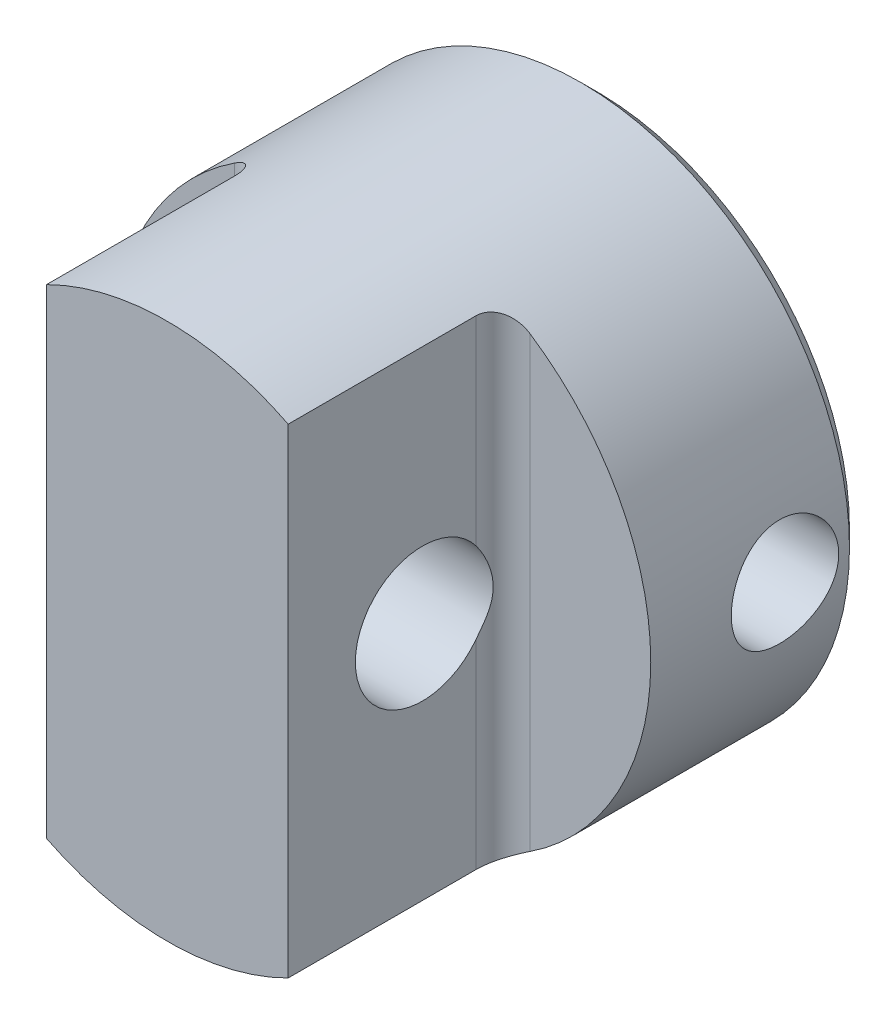
SolidWorks part; units mm, degrees
ref_plane "Спереди" through (0, 0, 0) normal (0, 0, 1) x (1, 0, 0)
ref_plane "Сверху" through (0, 0, 0) normal (0, 1, 0) x (1, 0, 0)
ref_plane "Справа" through (0, 0, 0) normal (1, 0, 0) x (0, 0, -1)
sketch "Эскиз1" plane through (0, 0, 0) normal (0, 0, 1) x (1, 0, 0)
  circle A0 centre (0, 0) radius 50
  dimension "D1" = 100
extrude "Бобышка-Вытянуть1" add sketch "Эскиз1" along normal blind 80
sketch "Эскиз2" plane through (0, 0, 80) normal (0, 0, 1) x (1, 0, 0)
  line L0 (0, 50) -> (0, -50) construction
  line L1 (-22.5, 44.6514) -> (-22.5, -44.6514)
  line L2 (22.5, 44.6514) -> (22.5, -44.6514)
  arc A0 (-22.5, 44.6514) -> (-22.5, -44.6514) centre (0, 0) ccw
  circle A1 centre (0, 0) radius 50 construction
  arc A2 (22.5, -44.6514) -> (22.5, 44.6514) centre (0, 0) ccw
  dimension "D3" = 45
extrude "Вырез-Вытянуть1" cut sketch "Эскиз2" against normal blind 40
fillet "Скругление1" radius 5 2 edges at (-22.5, 0, 40) (22.5, 0, 40)
sketch "Эскиз3" plane through (0, 0, 0) normal (1, 0, 0) x (0, 0, -1)
  line L0 (-80, 0) -> (45.1557, 0) construction
  line L1 (-80, 44.6514) -> (-80, -44.6514) construction
  circle A0 centre (-55, 0) radius 12.5
  dimension "D2" = 25
  dimension "D1" = 25
extrude "Вырез-Вытянуть2" cut sketch "Эскиз3" against normal through all and the other way through all
chamfer "Фаска1" distance 3 angle 45 1 edges at (50, 0, 0)
sketch "Эскиз4" plane through (0, 0, 0) normal (1, 0, 0) x (0, 0, -1)
  line L0 (-80, 0) -> (21.7466, 0) construction
  line L1 (-80, 44.6514) -> (-80, -44.6514) construction
  circle A0 centre (-15, 0) radius 10
  dimension "D1" = 20
  dimension "D2" = 15
extrude "Вырез-Вытянуть3" cut sketch "Эскиз4" against normal through all and the other way through all
